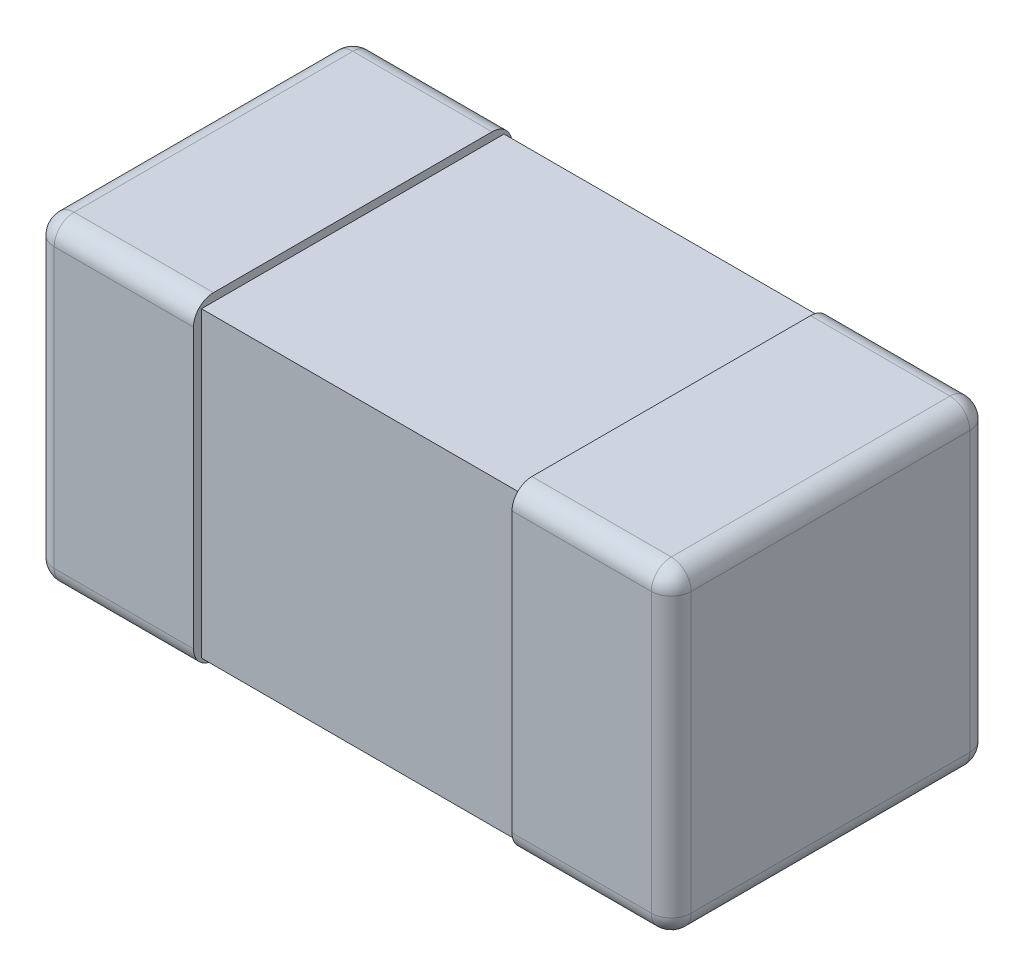
SolidWorks part; units mm, degrees
material "Silicon"
ref_plane "Front Plane" through (0, 0, 0) normal (0, 0, 1) x (1, 0, 0)
ref_plane "Top Plane" through (0, 0, 0) normal (0, 1, 0) x (1, 0, 0)
ref_plane "Right Plane" through (0, 0, 0) normal (1, 0, 0) x (0, 0, -1)
ref_plane "Board Plane" through (0, 0, 0) normal (0, 1, 0) x (1, 0, 0)
sketch "Sketch1" plane through (0, 0, 0) normal (0, 1, 0) x (1, 0, 0)
  line L0 (-60.4173, 0) -> (0, 0) construction
  line L1 (0, 0) -> (0, 108.4559) construction
  line L2 (0, -55) -> (0, 55) construction
  line L3 (-55, 0) -> (55, 0) construction
  line L4 (0.8, 0.4) -> (0.8, -0.4)
  line L5 (-0.8, 0.4) -> (0.8, 0.4)
  line L6 (-0.8, 0.4) -> (-0.8, -0.4)
  line L9 (-0.8, -0.4) -> (0.8, -0.4)
  point P14 (0, -0.4)
  point P15 (0, 0.4)
  point P16 (-0.8, 0)
  point P17 (0.8, 0)
  dimension "D1" = 1.6
  dimension "D2" = 0.8
extrude "Boss-Extrude1" add sketch "Sketch1" along normal blind 0.8
sketch "Sketch2" plane through (0, 0, 0) normal (1, 0, 0) x (0, 0, -1)
  line L0 (0.4, 0.8) -> (-0.4, 0.8)
  line L1 (0.4, 0.8) -> (-0.4, 0.8) construction
  line L2 (-0.4, 0) -> (-0.4, 0.8)
  line L3 (-0.4, 0) -> (-0.4, 0.8) construction
  line L4 (0.4, 0) -> (-0.4, 0)
  line L5 (0.4, 0) -> (-0.4, 0) construction
  line L6 (0.4, 0.8) -> (0.4, 0)
  line L7 (0.4, 0.8) -> (0.4, 0) construction
  line L8 (0.38, 0.78) -> (-0.38, 0.78)
  line L9 (-0.38, 0.02) -> (-0.38, 0.78)
  line L10 (0.38, 0.02) -> (-0.38, 0.02)
  line L11 (0.38, 0.78) -> (0.38, 0.02)
  dimension "D1" = 0.02
extrude "Cut-Extrude1" cut sketch "Sketch2" against normal offset from surface 0.4 and the other way offset from surface (0.4 mm away) 0.4 flip side to cut up to face at (-0.8, 0.4, 0) other way up to face at (0.8, 0.4, 0)
fillet "Fillet1" radius 0.05 16 edges at (0.8, 0.4, -0.4) (0.8, 0, 0) (0.8, 0.4, 0.4) (0.8, 0.8, 0) (-0.8, 0.4, -0.4) (-0.8, 0, 0) (-0.8, 0.4, 0.4) (-0.8, 0.8, 0) (-0.6, 0.8, 0.4) (-0.6, 0, 0.4) (-0.6, 0, -0.4) (-0.6, 0.8, -0.4) (0.6, 0, -0.4) (0.6, 0, 0.4) (0.6, 0.8, 0.4) (0.6, 0.8, -0.4)
